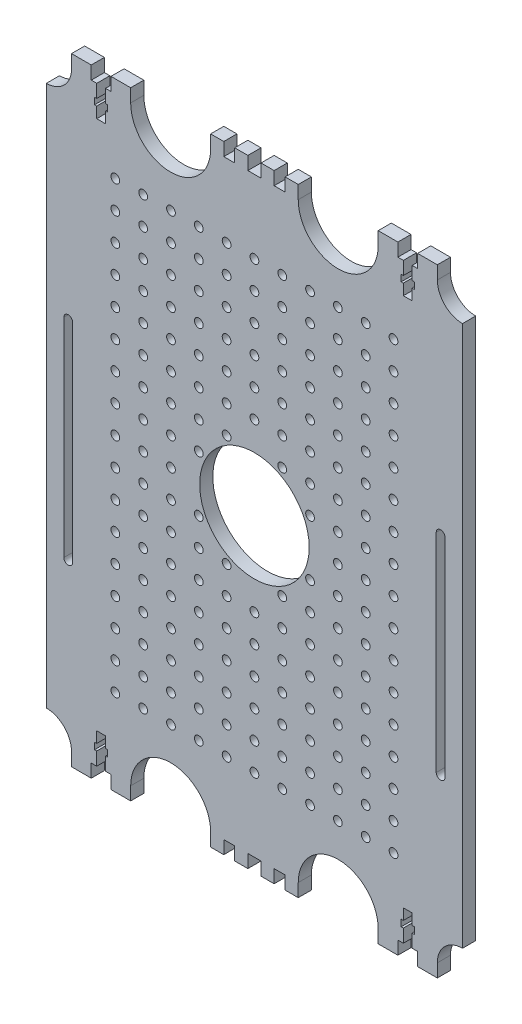
SolidWorks part; units mm, degrees
ref_plane "Plan de face" through (0, 0, 0) normal (0, 0, 1) x (1, 0, 0)
ref_plane "Plan de dessus" through (0, 0, 0) normal (0, 1, 0) x (1, 0, 0)
ref_plane "Plan de droite" through (0, 0, 0) normal (1, 0, 0) x (0, 0, -1)
sketch "Esquisse1" plane through (0, 0, 0) normal (0, 0, 1) x (1, 0, 0)
  line L0 (0, 135) -> (0, -135) construction
  line L1 (-95, 135) -> (95, 135)
  line L2 (-95, 135) -> (-95, -135)
  line L3 (-95, -135) -> (95, -135)
  line L4 (95, 135) -> (95, -135)
  dimension "D1" = 270
  dimension "D2" = 190
extrude "Boss.-Extru.1" add sketch "Esquisse1" along normal blind 6
sketch "Esquisse2" plane through (0, -135, 0) normal (0, -1, 0) x (1, 0, 0)
  line L0 (-70, 6) -> (-70, 0) construction
  line L1 (-95, 6) -> (95, 6) construction
  line L2 (-95, 0) -> (95, 0) construction
  line L3 (-95, 6) -> (-95, 0) construction
  line L5 (-83.5, 0) -> (-74.5, 0)
  line L6 (-83.5, 0) -> (-83.5, 6)
  line L7 (-83.5, 6) -> (-74.5, 6)
  line L8 (-74.5, 0) -> (-74.5, 6)
  line L9 (-65.5, 0) -> (-56.5, 0)
  line L10 (-65.5, 0) -> (-65.5, 6)
  line L11 (-65.5, 6) -> (-56.5, 6)
  line L12 (-56.5, 0) -> (-56.5, 6)
  dimension "D2" = 9
  dimension "D3" = 4.5
  dimension "D1" = 25
  dimension "D4" = 9
  dimension "D5" = 4.5
extrude "Boss.-Extru.2" add sketch "Esquisse2" along normal blind 6
sketch "Esquisse3" plane through (0, 0, 0) normal (0, 0, -1) x (-1, 0, 0)
  line L0 (74.5, -135) -> (65.5, -135) construction
  line L1 (68, -135) -> (72, -135)
  line L2 (68, -135) -> (68, -129)
  line L3 (68, -121) -> (72, -121)
  line L4 (72, -135) -> (72, -129)
  line L5 (70, -135) -> (70, -121) construction
  line L6 (72, -129) -> (73, -129)
  line L7 (67, -126) -> (68, -126)
  line L8 (67, -126) -> (67, -129)
  line L9 (67, -129) -> (68, -129)
  line L10 (73, -126) -> (73, -129)
  line L11 (72, -126) -> (72, -121)
  line L12 (72, -126) -> (73, -126)
  line L13 (68, -126) -> (68, -121)
  dimension "D1" = 14
  dimension "D2" = 4
  dimension "D3" = 6
  dimension "D4" = 3
  dimension "D5" = 1
  dimension "D6" = 1
extrude "Enlèv. mat.-Extru.1" cut sketch "Esquisse3" against normal blind 6
ref_plane "Plan1" through (0, 0, 0) normal (-1, 0, 0) x (0, 0, 1)
ref_plane "Plan2" through (0, 0, 0) normal (0, 1, 0) x (1, 0, 0)
mirror "Symétrie1" about plane through (0, 0, 0) normal (0, 1, 0) of "Enlèv. mat.-Extru.1", "Boss.-Extru.2"
mirror "Symétrie2" about plane through (0, 0, 0) normal (-1, 0, 0) of "Symétrie1", "Boss.-Extru.2", "Enlèv. mat.-Extru.1"
sketch "Esquisse4" plane through (0, -135, 0) normal (0, -1, 0) x (1, 0, 0)
  line L0 (-56.5, 6) -> (56.5, 6) construction
  line L1 (14, 6) -> (20, 6)
  line L2 (14, 6) -> (14, 0)
  line L3 (14, 0) -> (20, 0)
  line L4 (20, 6) -> (20, 0)
  line L5 (-56.5, 0) -> (56.5, 0) construction
  line L6 (20, 6) -> (0, 6) construction
  line L7 (0, 6) -> (-20, 6) construction
  line L9 (9, 6) -> (3, 6)
  line L10 (9, 6) -> (9, 0)
  line L11 (9, 0) -> (3, 0)
  line L12 (3, 6) -> (3, 0)
  line L13 (-20, 6) -> (-14, 6)
  line L14 (-20, 6) -> (-20, 0)
  line L15 (-20, 0) -> (-14, 0)
  line L16 (-14, 6) -> (-14, 0)
  line L17 (-9, 6) -> (-3, 6)
  line L18 (-9, 6) -> (-9, 0)
  line L19 (-9, 0) -> (-3, 0)
  line L20 (-3, 6) -> (-3, 0)
  dimension "D1" = 20
  dimension "D2" = 20
  dimension "D3" = 6
  dimension "D4" = 6
  dimension "D5" = 6
  dimension "D6" = 6
  dimension "D7" = 5
  dimension "D8" = 5
extrude "Boss.-Extru.3" add sketch "Esquisse4" along normal blind 6
mirror "Symétrie3" about plane through (0, 0, 0) normal (0, 1, 0) of "Boss.-Extru.3"
sketch "Esquisse6" plane through (0, 0, 6) normal (0, 0, 1) x (1, 0, 0)
  line L0 (-20, 135) -> (-56.5, 135) construction
  line L1 (56.5, 135) -> (20, 135) construction
  line L2 (-56.5, -135) -> (-20, -135) construction
  line L3 (20, -135) -> (56.5, -135) construction
  line L4 (-95, 135) -> (-95, -135) construction
  line L5 (-95, 135) -> (95, -135) construction
  circle A0 centre (-38.25, 135) radius 18.25
  circle A1 centre (38.25, 135) radius 18.25
  circle A2 centre (-38.25, -135) radius 18.25
  circle A3 centre (38.25, -135) radius 18.25
  circle A4 centre (-95, 135) radius 11.5
  circle A5 centre (95, 135) radius 11.5
  circle A6 centre (95, -135) radius 11.5
  circle A7 centre (-95, -135) radius 11.5
  circle A8 centre (0, 0) radius 25
  dimension "D1" = 50
extrude "Enlèv. mat.-Extru.2" cut sketch "Esquisse6" against normal blind 6
sketch "Esquisse7" plane through (0, 0, 6) normal (0, 0, 1) x (1, 0, 0)
  line L0 (85, 80.1372) -> (85, -89.5768) construction
  line L1 (95, -123.5) -> (95, 123.5) construction
  line L2 (85, 35) -> (85, -60) construction
  line L3 (87, 35) -> (87, -60)
  line L4 (83, 35) -> (83, -60)
  line L5 (74.5, 135) -> (72, 135) construction
  line L6 (72, -135) -> (74.5, -135) construction
  arc A0 (87, 35) -> (83, 35) centre (85, 35) ccw
  arc A1 (83, -60) -> (87, -60) centre (85, -60) ccw
  point P6 (85, -12.5)
  dimension "D2" = 2
  dimension "D1" = 10
  dimension "D3" = 100
  dimension "D4" = 75
extrude "Enlèv. mat.-Extru.3" cut sketch "Esquisse7" against normal blind 6
mirror "Symétrie4" about plane through (0, 0, 0) normal (1, 0, 0) of "Enlèv. mat.-Extru.3"
sketch "Esquisse8" plane through (0, 0, 6) normal (0, 0, 1) x (1, 0, 0)
  line L0 (0, -135) -> (0, 135) construction
  line L1 (-3, -135) -> (3, -135) construction
  line L2 (3, 135) -> (-3, 135) construction
  line L3 (0, 0) -> (-12.7, 0) construction
  circle A0 centre (0, 0) radius 2
  circle A1 centre (0, -12.7) radius 2
  circle A3 centre (0, -38.1) radius 2
  circle A4 centre (0, -50.8) radius 2
  circle A5 centre (0, -63.5) radius 2
  circle A6 centre (0, -76.2) radius 2
  circle A7 centre (0, -88.9) radius 2
  circle A8 centre (0, -101.6) radius 2
  circle A9 centre (-12.7, -12.7) radius 2
  circle A10 centre (-12.7, -25.4) radius 2
  circle A11 centre (-12.7, -38.1) radius 2
  circle A12 centre (-12.7, -50.8) radius 2
  circle A13 centre (-12.7, -63.5) radius 2
  circle A14 centre (-12.7, -76.2) radius 2
  circle A15 centre (-12.7, -88.9) radius 2
  circle A16 centre (-12.7, -101.6) radius 2
  circle A17 centre (-25.4, -12.7) radius 2
  circle A18 centre (-25.4, -25.4) radius 2
  circle A19 centre (-25.4, -38.1) radius 2
  circle A20 centre (-25.4, -50.8) radius 2
  circle A21 centre (-25.4, -63.5) radius 2
  circle A22 centre (-25.4, -76.2) radius 2
  circle A23 centre (-25.4, -88.9) radius 2
  circle A24 centre (-25.4, -101.6) radius 2
  circle A25 centre (-38.1, -12.7) radius 2
  circle A26 centre (-38.1, -25.4) radius 2
  circle A27 centre (-38.1, -38.1) radius 2
  circle A28 centre (-38.1, -50.8) radius 2
  circle A29 centre (-38.1, -63.5) radius 2
  circle A30 centre (-38.1, -76.2) radius 2
  circle A31 centre (-38.1, -88.9) radius 2
  circle A32 centre (-38.1, -101.6) radius 2
  circle A33 centre (-50.8, -12.7) radius 2
  circle A34 centre (-50.8, -25.4) radius 2
  circle A35 centre (-50.8, -38.1) radius 2
  circle A36 centre (-50.8, -50.8) radius 2
  circle A37 centre (-50.8, -63.5) radius 2
  circle A38 centre (-50.8, -76.2) radius 2
  circle A39 centre (-50.8, -88.9) radius 2
  circle A40 centre (-50.8, -101.6) radius 2
  circle A41 centre (-63.5, -12.7) radius 2
  circle A42 centre (-63.5, -25.4) radius 2
  circle A43 centre (-63.5, -38.1) radius 2
  circle A44 centre (-63.5, -50.8) radius 2
  circle A45 centre (-63.5, -63.5) radius 2
  circle A46 centre (-63.5, -76.2) radius 2
  circle A47 centre (-63.5, -88.9) radius 2
  circle A48 centre (-63.5, -101.6) radius 2
  circle A49 centre (-12.7, 0) radius 2
  circle A51 centre (-38.1, 0) radius 2
  circle A52 centre (-50.8, 0) radius 2
  circle A53 centre (-63.5, 0) radius 2
  circle A54 centre (0, 12.7) radius 2
  circle A55 centre (-12.7, 12.7) radius 2
  circle A56 centre (-25.4, 12.7) radius 2
  circle A57 centre (-38.1, 12.7) radius 2
  circle A58 centre (-50.8, 12.7) radius 2
  circle A59 centre (-63.5, 12.7) radius 2
  circle A61 centre (-12.7, 25.4) radius 2
  circle A62 centre (-25.4, 25.4) radius 2
  circle A63 centre (-38.1, 25.4) radius 2
  circle A64 centre (-50.8, 25.4) radius 2
  circle A65 centre (-63.5, 25.4) radius 2
  circle A66 centre (0, 38.1) radius 2
  circle A67 centre (-12.7, 38.1) radius 2
  circle A68 centre (-25.4, 38.1) radius 2
  circle A69 centre (-38.1, 38.1) radius 2
  circle A70 centre (-50.8, 38.1) radius 2
  circle A71 centre (-63.5, 38.1) radius 2
  circle A72 centre (0, 50.8) radius 2
  circle A73 centre (-12.7, 50.8) radius 2
  circle A74 centre (-25.4, 50.8) radius 2
  circle A75 centre (-38.1, 50.8) radius 2
  circle A76 centre (-50.8, 50.8) radius 2
  circle A77 centre (-63.5, 50.8) radius 2
  circle A78 centre (0, 63.5) radius 2
  circle A79 centre (-12.7, 63.5) radius 2
  circle A80 centre (-25.4, 63.5) radius 2
  circle A81 centre (-38.1, 63.5) radius 2
  circle A82 centre (-50.8, 63.5) radius 2
  circle A83 centre (-63.5, 63.5) radius 2
  circle A84 centre (0, 76.2) radius 2
  circle A85 centre (-12.7, 76.2) radius 2
  circle A86 centre (-25.4, 76.2) radius 2
  circle A87 centre (-38.1, 76.2) radius 2
  circle A88 centre (-50.8, 76.2) radius 2
  circle A89 centre (-63.5, 76.2) radius 2
  circle A90 centre (0, 88.9) radius 2
  circle A91 centre (-12.7, 88.9) radius 2
  circle A92 centre (-25.4, 88.9) radius 2
  circle A93 centre (-38.1, 88.9) radius 2
  circle A94 centre (-50.8, 88.9) radius 2
  circle A95 centre (-63.5, 88.9) radius 2
  circle A96 centre (0, 101.6) radius 2
  circle A97 centre (-12.7, 101.6) radius 2
  circle A98 centre (-25.4, 101.6) radius 2
  circle A99 centre (-38.1, 101.6) radius 2
  circle A100 centre (-50.8, 101.6) radius 2
  circle A101 centre (-63.5, 101.6) radius 2
  circle A102 centre (12.7, 101.6) radius 2
  circle A103 centre (12.7, 88.9) radius 2
  circle A104 centre (12.7, 76.2) radius 2
  circle A105 centre (12.7, 63.5) radius 2
  circle A106 centre (12.7, 50.8) radius 2
  circle A107 centre (12.7, 38.1) radius 2
  circle A108 centre (12.7, 25.4) radius 2
  circle A109 centre (12.7, 12.7) radius 2
  circle A110 centre (12.7, 0) radius 2
  circle A111 centre (12.7, -12.7) radius 2
  circle A112 centre (12.7, -25.4) radius 2
  circle A113 centre (12.7, -38.1) radius 2
  circle A114 centre (12.7, -50.8) radius 2
  circle A115 centre (12.7, -63.5) radius 2
  circle A116 centre (12.7, -76.2) radius 2
  circle A117 centre (12.7, -88.9) radius 2
  circle A118 centre (12.7, -101.6) radius 2
  circle A119 centre (25.4, 101.6) radius 2
  circle A120 centre (25.4, 88.9) radius 2
  circle A121 centre (25.4, 76.2) radius 2
  circle A122 centre (25.4, 63.5) radius 2
  circle A123 centre (25.4, 50.8) radius 2
  circle A124 centre (25.4, 38.1) radius 2
  circle A125 centre (25.4, 25.4) radius 2
  circle A126 centre (25.4, 12.7) radius 2
  circle A128 centre (25.4, -12.7) radius 2
  circle A129 centre (25.4, -25.4) radius 2
  circle A130 centre (25.4, -38.1) radius 2
  circle A131 centre (25.4, -50.8) radius 2
  circle A132 centre (25.4, -63.5) radius 2
  circle A133 centre (25.4, -76.2) radius 2
  circle A134 centre (25.4, -88.9) radius 2
  circle A135 centre (25.4, -101.6) radius 2
  circle A136 centre (38.1, 101.6) radius 2
  circle A137 centre (38.1, 88.9) radius 2
  circle A138 centre (38.1, 76.2) radius 2
  circle A139 centre (38.1, 63.5) radius 2
  circle A140 centre (38.1, 50.8) radius 2
  circle A141 centre (38.1, 38.1) radius 2
  circle A142 centre (38.1, 25.4) radius 2
  circle A143 centre (38.1, 12.7) radius 2
  circle A144 centre (38.1, 0) radius 2
  circle A145 centre (38.1, -12.7) radius 2
  circle A146 centre (38.1, -25.4) radius 2
  circle A147 centre (38.1, -38.1) radius 2
  circle A148 centre (38.1, -50.8) radius 2
  circle A149 centre (38.1, -63.5) radius 2
  circle A150 centre (38.1, -76.2) radius 2
  circle A151 centre (38.1, -88.9) radius 2
  circle A152 centre (38.1, -101.6) radius 2
  circle A153 centre (50.8, 101.6) radius 2
  circle A154 centre (50.8, 88.9) radius 2
  circle A155 centre (50.8, 76.2) radius 2
  circle A156 centre (50.8, 63.5) radius 2
  circle A157 centre (50.8, 50.8) radius 2
  circle A158 centre (50.8, 38.1) radius 2
  circle A159 centre (50.8, 25.4) radius 2
  circle A160 centre (50.8, 12.7) radius 2
  circle A161 centre (50.8, 0) radius 2
  circle A162 centre (50.8, -12.7) radius 2
  circle A163 centre (50.8, -25.4) radius 2
  circle A164 centre (50.8, -38.1) radius 2
  circle A165 centre (50.8, -50.8) radius 2
  circle A166 centre (50.8, -63.5) radius 2
  circle A167 centre (50.8, -76.2) radius 2
  circle A168 centre (50.8, -88.9) radius 2
  circle A169 centre (50.8, -101.6) radius 2
  circle A170 centre (63.5, 101.6) radius 2
  circle A171 centre (63.5, 88.9) radius 2
  circle A172 centre (63.5, 76.2) radius 2
  circle A173 centre (63.5, 63.5) radius 2
  circle A174 centre (63.5, 50.8) radius 2
  circle A175 centre (63.5, 38.1) radius 2
  circle A176 centre (63.5, 25.4) radius 2
  circle A177 centre (63.5, 12.7) radius 2
  circle A178 centre (63.5, 0) radius 2
  circle A179 centre (63.5, -12.7) radius 2
  circle A180 centre (63.5, -25.4) radius 2
  circle A181 centre (63.5, -38.1) radius 2
  circle A182 centre (63.5, -50.8) radius 2
  circle A183 centre (63.5, -63.5) radius 2
  circle A184 centre (63.5, -76.2) radius 2
  circle A185 centre (63.5, -88.9) radius 2
  circle A186 centre (63.5, -101.6) radius 2
  circle A187 centre (-25.4, 0) radius 2 [skipped]
  arc A188 (0, -27.4) -> (0, -23.4) centre (0, -25.4) ccw [skipped]
  arc A189 (0, 27.4) -> (0, 23.4) centre (0, 25.4) ccw [skipped]
  circle A190 centre (25.4, 0) radius 2 [skipped]
  dimension "D1" = 4
  dimension "D4" = 12.7
  dimension "D2" = 9
  dimension "D3" = 6
  dimension "D5" = 9
  dimension "D6" = 6
extrude "Enlèv. mat.-Extru.4" cut sketch "Esquisse8" against normal blind 6
